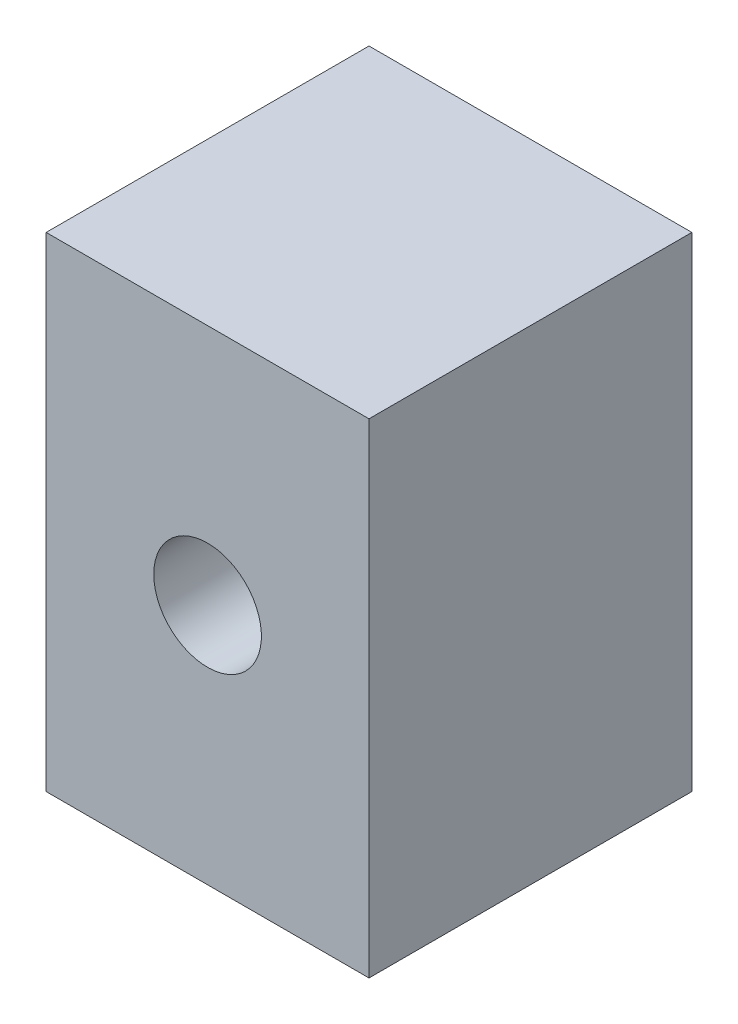
SolidWorks part; units mm, degrees
ref_plane "Front Plane" through (0, 0, 0) normal (0, 0, 1) x (1, 0, 0)
ref_plane "Top Plane" through (0, 0, 0) normal (0, 1, 0) x (1, 0, 0)
ref_plane "Right Plane" through (0, 0, 0) normal (1, 0, 0) x (0, 0, -1)
sketch "Sketch1" plane through (0, 0, 0) normal (0, 0, 1) x (1, 0, 0)
  line L1 (-38.1, -57.15) -> (38.1, -57.15)
  line L2 (-38.1, -57.15) -> (-38.1, 57.15)
  line L3 (-38.1, 57.15) -> (38.1, 57.15)
  line L4 (38.1, -57.15) -> (38.1, 57.15)
  line L5 (-38.1, -57.15) -> (38.1, 57.15) construction
  line L6 (-38.1, 57.15) -> (38.1, -57.15) construction
  circle A0 centre (0, 0) radius 12.7
  point P0 (0, 0)
  dimension "D3" = 25.4
  dimension "D1" = 76.2
  dimension "D2" = 114.3
extrude "Boss-Extrude1" add sketch "Sketch1" along normal mid plane 76.2
